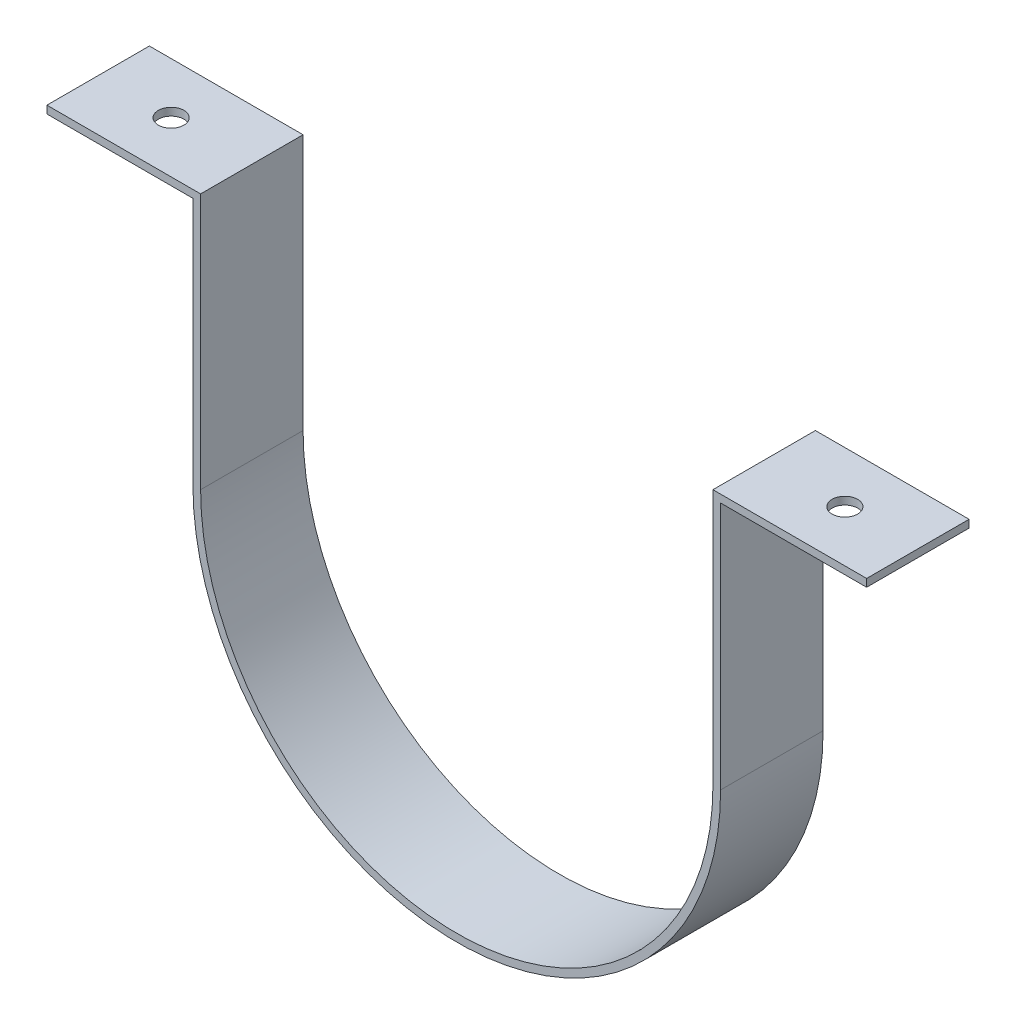
SolidWorks part; units mm, degrees
ref_plane "Plano frontal" through (0, 0, 0) normal (0, 0, 1) x (1, 0, 0)
ref_plane "Plano superior" through (0, 0, 0) normal (0, 1, 0) x (1, 0, 0)
ref_plane "Plano direito" through (0, 0, 0) normal (1, 0, 0) x (0, 0, -1)
sketch "Esboço1" plane through (0, 0, 0) normal (0, 0, 1) x (1, 0, 0)
  line L0 (90.1784, 42.2792) -> (193.1784, 42.2792) construction
  line L1 (191.6784, 42.2792) -> (191.6784, -7.7208)
  line L2 (91.6784, 42.2792) -> (91.6784, -7.7208)
  line L3 (193.1784, -7.7208) -> (193.1784, 40.7792)
  line L8 (141.6784, 43.6292) -> (141.6784, 43.7792) construction
  line L11 (90.1784, -7.7208) -> (90.1784, 40.7792)
  line L15 (90.1784, 40.7792) -> (61.6784, 40.7792)
  line L17 (91.6784, 42.2792) -> (61.6784, 42.2792)
  line L18 (61.6784, 40.7792) -> (61.6784, 42.2792)
  line L19 (193.1784, 40.7792) -> (221.6784, 40.7792)
  line L21 (191.6784, 42.2792) -> (221.6784, 42.2792)
  line L22 (221.6784, 40.7792) -> (221.6784, 42.2792)
  circle A0 centre (141.6784, -7.7208) radius 50 construction
  arc A1 (91.6784, -7.7208) -> (191.6784, -7.7208) centre (141.6784, -7.7208) ccw
  arc A2 (90.1784, -7.7208) -> (193.1784, -7.7208) centre (141.6784, -7.7208) ccw
  circle A3 centre (141.6784, -7.7208) radius 51.5 construction
  circle A4 centre (141.6784, -7.7208) radius 50 construction
  point P27 (141.6784, 42.2792)
  dimension "D5" = 1.5
  dimension "D2" = 28.5
  dimension "D3" = 28.5
  dimension "D6" = 1.5
  dimension "D1" = 1.5
extrude "Ressalto-extrusão1" add sketch "Esboço1" along normal blind 20
sketch "Esboço2" plane through (0, 40.7792, 0) normal (0, -1, 0) x (1, 0, 0)
  line L0 (61.6784, 20) -> (90.1784, 0) construction
  line L1 (193.1784, 20) -> (221.6784, 0) construction
  line L4 (61.6784, 0) -> (90.1784, 0)
  line L5 (90.1784, 0) -> (90.1784, 20)
  line L6 (90.1784, 20) -> (61.6784, 20)
  line L7 (61.6784, 20) -> (61.6784, 0)
  line L8 (61.6784, 0) -> (90.1784, 0)
  line L9 (90.1784, 0) -> (90.1784, 20)
  line L10 (90.1784, 20) -> (61.6784, 20)
  line L11 (61.6784, 20) -> (61.6784, 0)
  line L12 (193.1784, 0) -> (221.6784, 0)
  line L13 (221.6784, 0) -> (221.6784, 20)
  line L14 (221.6784, 20) -> (193.1784, 20)
  line L15 (193.1784, 20) -> (193.1784, 0)
  line L16 (193.1784, 0) -> (221.6784, 0)
  line L17 (221.6784, 0) -> (221.6784, 20)
  line L18 (221.6784, 20) -> (193.1784, 20)
  line L19 (193.1784, 20) -> (193.1784, 0)
  circle A0 centre (75.9284, 10) radius 2.5
  circle A1 centre (207.4284, 10) radius 2.5
  dimension "D3" = 5
  dimension "D1" = 0
  dimension "D2" = 0
extrude "Corte-extrusão2" cut sketch "Esboço2" against normal blind 2 contours A0 | A1
